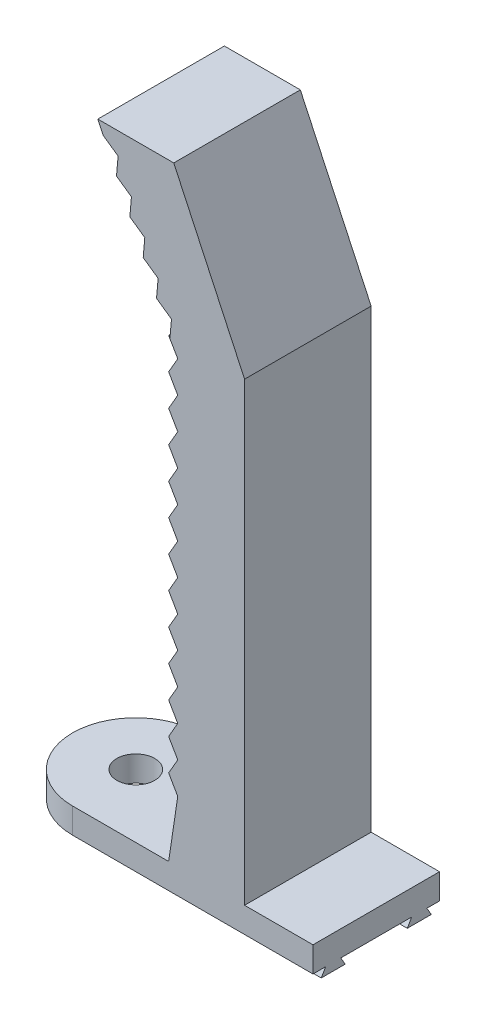
SolidWorks part; units mm, degrees
ref_plane "Front Plane" through (0, 0, 0) normal (0, 0, 1) x (1, 0, 0)
ref_plane "Top Plane" through (0, 0, 0) normal (0, 1, 0) x (1, 0, 0)
ref_plane "Right Plane" through (0, 0, 0) normal (1, 0, 0) x (0, 0, -1)
sketch "Sketch1" plane through (0, 0, 0) normal (0, 1, 0) x (1, 0, 0)
  line L0 (60, 25) -> (-35, 25)
  line L1 (-35, -25) -> (60, -25)
  line L2 (60, -25) -> (60, 25)
  arc A0 (-35, 25) -> (-35, -25) centre (-35, 0) ccw
  circle A1 centre (-35, 0) radius 7.5
  point P4 (-60, 0)
  dimension "D4" = 120
  dimension "D5" = 15
  dimension "D1" = 60
  dimension "D2" = 50
  dimension "D3" = 25
extrude "Boss-Extrude1" add sketch "Sketch1" along normal blind 10
sketch "Sketch2" plane through (60, 0, 0) normal (1, 0, 0) x (0, 0, -1)
  line L0 (-20, 0) -> (-21.7321, -3)
  line L1 (-25, 0) -> (25, 0) construction
  line L2 (-21.7321, -3) -> (-12.2679, -3)
  line L3 (-12.2679, -3) -> (-14, 0)
  line L4 (-14, 0) -> (-20, 0)
  line L5 (0, 0) -> (0, -16.3761) construction
  line L6 (21.7321, -3) -> (12.2679, -3)
  line L7 (14, 0) -> (20, 0)
  line L8 (20, 0) -> (21.7321, -3)
  line L9 (12.2679, -3) -> (14, 0)
  dimension "D1" = 60
  dimension "D2" = 60
  dimension "D3" = 5
  dimension "D4" = 6
  dimension "D5" = 3
extrude "Boss-Extrude2" add sketch "Sketch2" against normal blind 80
sketch "Sketch3" plane through (0, 0, 0) normal (0, 0, 1) x (1, 0, 0)
  line L1 (-35, 10) -> (60, 10) construction
  line L17 (2.9785, 10) -> (2.9785, 190)
  line L18 (2.9785, 190) -> (-25, 250)
  line L19 (-25, 250) -> (5, 250)
  line L20 (5, 250) -> (32.9785, 190)
  line L21 (32.9785, 190) -> (32.9785, 10)
  line L22 (60, 10) -> (60, 0) construction
  line L23 (2.9785, 10) -> (32.9785, 10)
  point P9 (5, 189.0157)
  dimension "D1" = 85
  dimension "D2" = 55
  dimension "D3" = 240
  dimension "D4" = 180
  dimension "D5" = 180
  dimension "D6" = 155
  dimension "D7" = 155
extrude "Boss-Extrude3" add sketch "Sketch3" along normal mid plane 50
scale "Scale2" scale about centroid uniform scaling yes scale factor 0.2004
sketch "Sketch9" plane through (0, 0, 5.01) normal (0, 0, 1) x (1, 0, 0)
  line L0 (11.0772, 127.8495) -> (11.7989, 126.5995)
  line L1 (11.7989, 126.5995) -> (11.0772, 125.3495)
  line L2 (11.0772, 127.8495) -> (11.0772, 91.7775) construction
  line L3 (11.0772, 122.8495) -> (11.0772, 127.8495)
  line L4 (11.0772, 125.3495) -> (11.851, 125.3495) construction
  line L5 (11.7989, 124.0995) -> (11.0772, 125.3495)
  line L6 (11.0772, 122.8495) -> (11.7989, 124.0995)
  line L7 (11.0772, 122.8495) -> (12, 122.8495) construction
  line L8 (11.0772, 122.8495) -> (11.7989, 121.5995)
  line L9 (11.7989, 121.5995) -> (11.0772, 120.3495)
  line L10 (11.0772, 122.8495) -> (11.0772, 112.8495)
  line L11 (11.7989, 119.0995) -> (11.0772, 120.3495)
  line L12 (11.0772, 117.8495) -> (11.7989, 119.0995)
  line L13 (11.0772, 117.8495) -> (12.4574, 117.8495) construction
  line L14 (11.0772, 117.8495) -> (11.7989, 116.5995)
  line L15 (11.7989, 116.5995) -> (11.0772, 115.3495)
  line L16 (11.7989, 114.0995) -> (11.0772, 115.3495)
  line L17 (11.0772, 112.8495) -> (11.7989, 114.0995)
  line L18 (11.0772, 112.8495) -> (11.7989, 111.5995)
  line L19 (11.7989, 111.5995) -> (11.0772, 110.3495)
  line L20 (11.0772, 112.8495) -> (11.0772, 107.8495)
  line L21 (11.7989, 109.0995) -> (11.0772, 110.3495)
  line L22 (11.0772, 107.8495) -> (11.7989, 109.0995)
  line L23 (11.0772, 107.8495) -> (12.8923, 107.8495) construction
  line L24 (11.0772, 107.8495) -> (11.7989, 106.5995)
  line L25 (11.7989, 106.5995) -> (11.0772, 105.3495)
  line L28 (11.0772, 107.8495) -> (11.0772, 105.3495)
  line L30 (5.893, 138.9672) -> (7.0753, 138.1393)
  line L31 (7.0753, 138.1393) -> (6.9495, 136.7014)
  line L32 (5.4704, 139.8735) -> (11.0772, 127.8495) construction
  line L33 (6.9495, 136.7014) -> (-6.6964, 130.3382) construction
  line L34 (8.1319, 135.8735) -> (6.9495, 136.7014)
  line L35 (8.0061, 134.4356) -> (8.1319, 135.8735)
  line L36 (8.0061, 134.4356) -> (-5.4547, 128.1588) construction
  line L37 (8.0061, 134.4356) -> (9.1884, 133.6078)
  line L38 (9.1884, 133.6078) -> (9.0626, 132.1699)
  line L39 (10.245, 131.342) -> (9.0626, 132.1699)
  line L40 (10.1192, 129.9041) -> (10.245, 131.342)
  line L41 (10.1192, 129.9041) -> (-2.4851, 124.0266) construction
  line L42 (10.1192, 129.9041) -> (11.3015, 129.0762)
  line L43 (11.3015, 129.0762) -> (11.1757, 127.6383)
  line L44 (5.893, 138.9672) -> (6.9495, 136.7014)
  line L45 (6.9495, 136.7014) -> (8.0061, 134.4356)
  line L46 (8.0061, 134.4356) -> (9.0626, 132.1699)
  line L47 (10.1192, 129.9041) -> (11.1757, 127.6383)
  line L48 (11.0772, 127.8495) -> (11.0772, 125.3495)
  line L49 (11.0772, 125.3495) -> (11.0772, 122.8495)
  line L50 (11.0772, 120.3495) -> (11.0772, 117.8495)
  line L51 (11.0772, 117.8495) -> (11.0772, 115.3495)
  line L52 (11.0772, 115.3495) -> (11.0772, 112.8495)
  line L53 (11.0772, 110.3495) -> (11.0772, 112.8495)
  line L54 (11.0772, 107.8495) -> (11.0772, 110.3495)
  line L55 (11.0772, 105.3495) -> (11.0772, 107.8495)
  line L56 (11.0772, 105.3495) -> (13.239, 105.3495) construction
  line L57 (11.7989, 104.0995) -> (11.0772, 105.3495)
  line L58 (11.0772, 102.8495) -> (11.7989, 104.0995)
  line L59 (11.0772, 102.8495) -> (11.7989, 101.5995)
  line L60 (11.7989, 101.5995) -> (11.0772, 100.3495)
  line L61 (11.7989, 99.0995) -> (11.0772, 100.3495)
  line L62 (11.0772, 97.8495) -> (11.7989, 99.0995)
  line L63 (11.0772, 97.8495) -> (11.7989, 96.5995)
  line L64 (11.7989, 96.5995) -> (11.0772, 91.7775)
  line L65 (11.0772, 91.7775) -> (11.0772, 97.8495)
  line L66 (11.0772, 100.3495) -> (11.0772, 102.8495)
  line L67 (11.0772, 100.3495) -> (11.0772, 102.8495)
  line L68 (11.0772, 100.3495) -> (11.0772, 102.8495)
  line L69 (11.7989, 101.5995) -> (11.0772, 100.3495)
  line L70 (11.0772, 100.3495) -> (11.0772, 102.8495)
  dimension "D1" = 30
  dimension "D2" = 120
  dimension "D3" = 2.5
  dimension "D4" = 30
  dimension "D5" = 30
  dimension "D6" = 1
  dimension "D7" = 2.5
extrude "Cut-Extrude9" cut sketch "Sketch9" against normal blind 20
sketch "Sketch10" plane through (0, 0, -5.01) normal (0, 0, -1) x (-1, 0, 0)
  line L0 (-11.0772, 102.8495) -> (-11.7989, 101.5995)
  line L1 (-11.7989, 101.5995) -> (-11.0772, 100.3495)
  line L2 (-11.0772, 102.8495) -> (-11.0772, 97.8495) construction
  line L3 (-11.0772, 100.3495) -> (-12.4989, 100.3495) construction
  line L4 (-11.0772, 97.8495) -> (-11.7989, 99.0995)
  line L5 (-11.7989, 99.0995) -> (-11.0772, 100.3495)
  line L6 (-11.0772, 102.8495) -> (-11.0772, 100.3495)
  line L7 (-11.0772, 100.3495) -> (-11.0772, 97.8495)
  line M37 (-11.0772, 97.8495) -> (-11.0772, 102.8495)
  dimension "D1" = 30
  dimension "D2" = 30
extrude "Cut-Extrude10" cut sketch "Sketch10" against normal blind 20 contours L0 L1 M37 | L5 L4 M37
